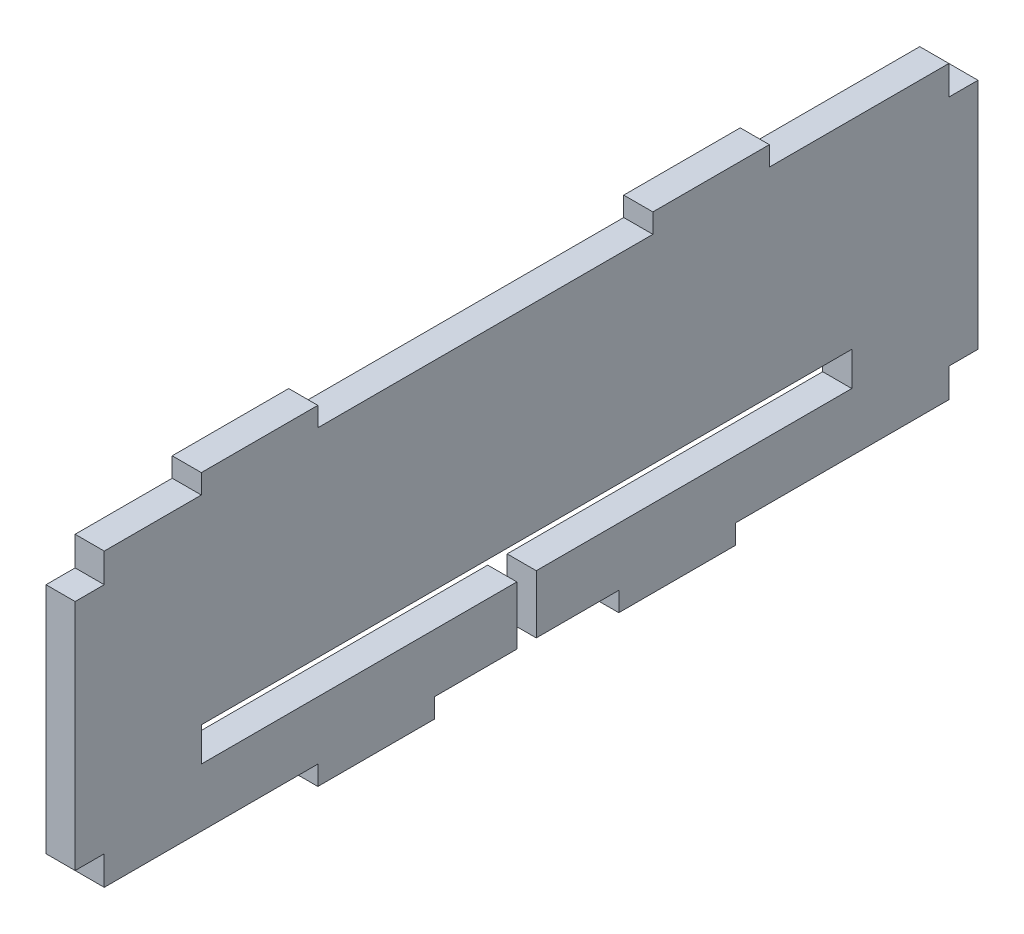
SolidWorks part; units mm, degrees
ref_plane "Front Plane" through (0, 0, 0) normal (0, 0, 1) x (1, 0, 0)
ref_plane "Top Plane" through (0, 0, 0) normal (0, 1, 0) x (1, 0, 0)
ref_plane "Right Plane" through (0, 0, 0) normal (1, 0, 0) x (0, 0, -1)
sketch "Sketch1" plane through (0, 0, 0) normal (1, 0, 0) x (0, 0, -1)
  line L0 (0, 0) -> (0, -32841.5669)
  line L1 (0, 0) -> (32841.5669, 0)
  line L2 (0, 5) -> (3, 5)
  line L3 (0, 0) -> (93, 0)
  line L4 (0, 0) -> (0, 34)
  line L5 (0, 34) -> (93, 34)
  line L6 (93, 0) -> (93, 34)
  line L11 (3, 5) -> (3, 2)
  line L12 (3, 2) -> (25, 2)
  line L13 (25, 2) -> (25, 0)
  line L14 (25, 0) -> (37, 0)
  line L15 (37, 0) -> (37, 2)
  line L16 (13, 8) -> (45.5, 8)
  line L17 (45.5, 8) -> (45.5, 2)
  line L18 (45.5, 2) -> (37, 2)
  line L19 (13, 8) -> (13, 11.5)
  line L20 (13, 11.5) -> (80, 11.5)
  line L21 (80, 11.5) -> (80, 8)
  line L22 (80, 8) -> (47.5, 8)
  line L23 (47.5, 8) -> (47.5, 2)
  line L24 (47.5, 2) -> (56, 2)
  line L25 (56, 2) -> (56, 0)
  line L26 (56, 0) -> (68, 0)
  line L27 (68, 0) -> (68, 2)
  line L28 (68, 2) -> (90, 2)
  line L29 (90, 2) -> (90, 5)
  line L30 (90, 5) -> (93, 5)
  line L31 (0, 29) -> (3, 29)
  line L32 (3, 29) -> (3, 32)
  line L33 (3, 32) -> (13, 32)
  line L34 (13, 32) -> (13, 34)
  line L35 (13, 34) -> (25, 34)
  line L36 (25, 34) -> (25, 32)
  line L37 (25, 32) -> (59.51, 32)
  line L38 (59.51, 32) -> (59.51, 34)
  line L39 (59.51, 34) -> (71.51, 34)
  line L40 (71.51, 34) -> (71.51, 32)
  line L41 (71.51, 32) -> (90, 32)
  line L42 (90, 32) -> (90, 29)
  line L43 (90, 29) -> (93, 29)
  dimension "D1" = 34
  dimension "D2" = 93
  dimension "D3" = 2
  dimension "D4" = 3
  dimension "D5" = 3
  dimension "D6" = 2
  dimension "D7" = 12
  dimension "D8" = 22
  dimension "D9" = 3
  dimension "D10" = 3
  dimension "D11" = 12
  dimension "D12" = 22
  dimension "D13" = 12
  dimension "D14" = 2
  dimension "D15" = 2
  dimension "D16" = 12
  dimension "D17" = 2
  dimension "D18" = 3
  dimension "D19" = 5
  dimension "D20" = 3
  dimension "D21" = 12
  dimension "D22" = 12
  dimension "D23" = 3.5
  dimension "D24" = 6
extrude "Boss-Extrude1" add sketch "Sketch1" along normal blind 3 contours L43 L42 L41 L40 L5 L38 L37 L36 L34 L33 L32 L31 L4 L2 L11 L12 L13 L3 L15 L18 L17 L16 L19 L20 L21 L22 L23 L24 L25 L27 L28 L29 L30 L6
